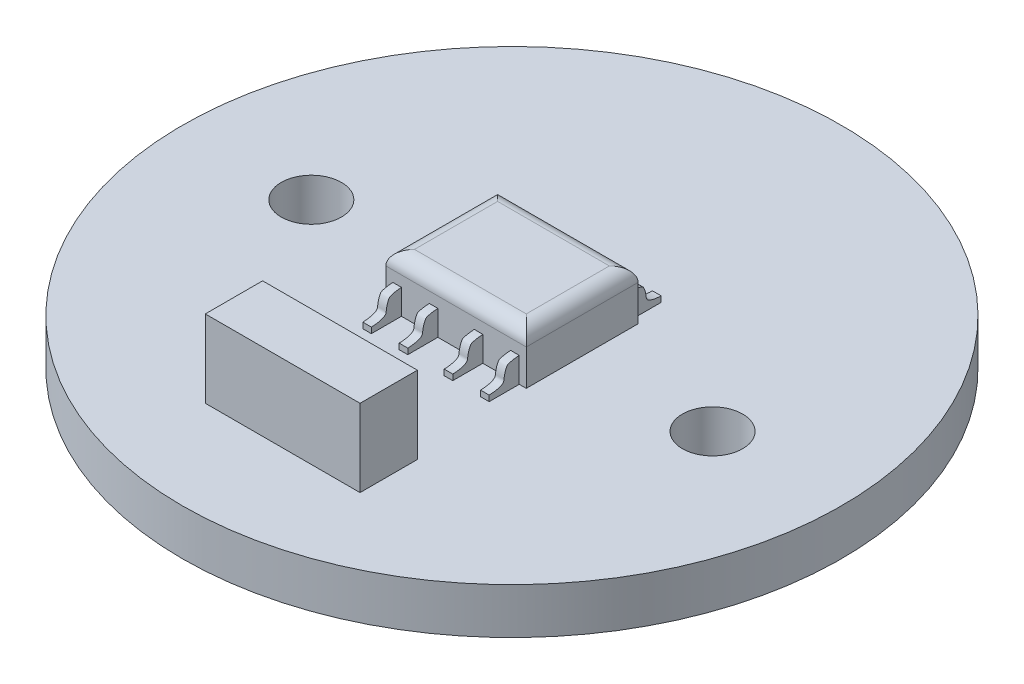
SolidWorks part; units mm, degrees
ref_plane "Front Plane" through (0, 0, 0) normal (0, 0, 1) x (1, 0, 0)
ref_plane "Top Plane" through (0, 0, 0) normal (0, 1, 0) x (1, 0, 0)
ref_plane "Right Plane" through (0, 0, 0) normal (1, 0, 0) x (0, 0, -1)
sketch "Sketch1" plane through (0, 0, 0) normal (0, 1, 0) x (1, 0, 0)
  circle A0 centre (0, 0) radius 11.5
  circle A1 centre (0, 0) radius 7 construction
  circle A2 centre (-7, 0) radius 1.05
  circle A3 centre (7, 0) radius 1.05
  dimension "D1" = 23
  dimension "D2" = 14
  dimension "D3" = 2.1
extrude "Boss-Extrude1" add sketch "Sketch1" along normal blind 1.6
sketch "Sketch2" plane through (0, 1.6, 0) normal (0, 1, 0) x (1, 0, 0)
  line L0 (0, -0.88) -> (0, 0.88) construction
  line L1 (-2.45, 1.95) -> (2.45, 1.95)
  line L2 (-2.45, 1.95) -> (-2.45, -1.95)
  line L3 (-2.45, -1.95) -> (2.45, -1.95)
  line L4 (2.45, 1.95) -> (2.45, -1.95)
  line L5 (-2.45, 1.95) -> (2.45, -1.95) construction
  line L6 (-2.45, -1.95) -> (2.45, 1.95) construction
  point P0 (0, 0)
  point P7 (0, 0)
  dimension "D1" = 4.9
  dimension "D2" = 3.9
extrude "Boss-Extrude2" add sketch "Sketch2" along normal blind 1.75
sketch "Sketch3" plane through (0, 1.6, 0) normal (0, 1, 0) x (1, 0, 0)
  line L0 (-2.45, -1.95) -> (2.45, -1.95) construction
  line L1 (-2.205, -1.95) -> (-1.905, -1.95)
  line L2 (-2.205, -1.95) -> (-2.205, -3)
  line L3 (-2.205, -3) -> (-1.905, -3)
  line L4 (-1.905, -1.95) -> (-1.905, -3)
  line L5 (0, -0.88) -> (0, 0.88) construction
  line L6 (-0.935, -1.95) -> (-0.635, -1.95)
  line L7 (-0.935, -1.95) -> (-0.935, -3)
  line L8 (-0.935, -3) -> (-0.635, -3)
  line L9 (-0.635, -1.95) -> (-0.635, -3)
  point P10 (-2.055, -3)
  point P11 (-0.785, -3)
  dimension "D1" = 1.05
  dimension "D2" = 1.27
  dimension "D3" = 0.3
  dimension "D4" = 0.635
extrude "Boss-Extrude3" add sketch "Sketch3" along normal blind 0.875
mirror "Mirror1" about plane through (0, 0, 0) normal (1, 0, 0) of "Boss-Extrude3"
mirror "Mirror2" about plane through (0, 0, 0) normal (0, 0, 1) of "Mirror1", "Boss-Extrude3"
fillet "Fillet1" radius 0.5 4 edges at (0, 3.35, 1.95) (-2.45, 3.35, 0) (0, 3.35, -1.95) (2.45, 3.35, 0)
sketch "Sketch4" plane through (2.205, 0, 0) normal (1, 0, 0) x (0, 0, -1)
  line L1 (3, 2.475) -> (3, 1.6) construction
  line L5 (1.95, 2.475) -> (3, 2.475)
  line L6 (3, 2.475) -> (3, 1.8)
  spline S0 degree 3 poles (1.95, 2.475) (2.1128, 2.4691) (2.3554, 2.4188) (2.4061, 2.3158) (2.472, 2.178) (2.4908, 1.8708) (2.8009, 1.8006) (3, 1.8) knots 0 0 0 0 0.320657 0.400503 0.754238 0.818609 1 1 1 1
extrude "Cut-Extrude1" cut sketch "Sketch4" against normal through all both and the other way through all
mirror "Mirror3" about plane through (0, 0, 0) normal (0, 0, 1) of "Cut-Extrude1"
sketch "Sketch5" plane through (0, 1.6, 0) normal (0, 1, 0) x (1, 0, 0)
  line L0 (0, -0.88) -> (0, 0.88) construction
  line L1 (2.7, -8) -> (-2.7, -8)
  line L2 (2.7, -8) -> (2.7, -6)
  line L3 (2.7, -6) -> (-2.7, -6)
  line L4 (-2.7, -8) -> (-2.7, -6)
  line L5 (2.7, -8) -> (-2.7, -6) construction
  line L6 (2.7, -6) -> (-2.7, -8) construction
  circle A0 centre (0, 0) radius 11.5 construction
  point P0 (0, -7)
  dimension "D3" = 3.5
  dimension "D1" = 2
  dimension "D2" = 5.4
extrude "Boss-Extrude4" add sketch "Sketch5" along normal blind 2.7
